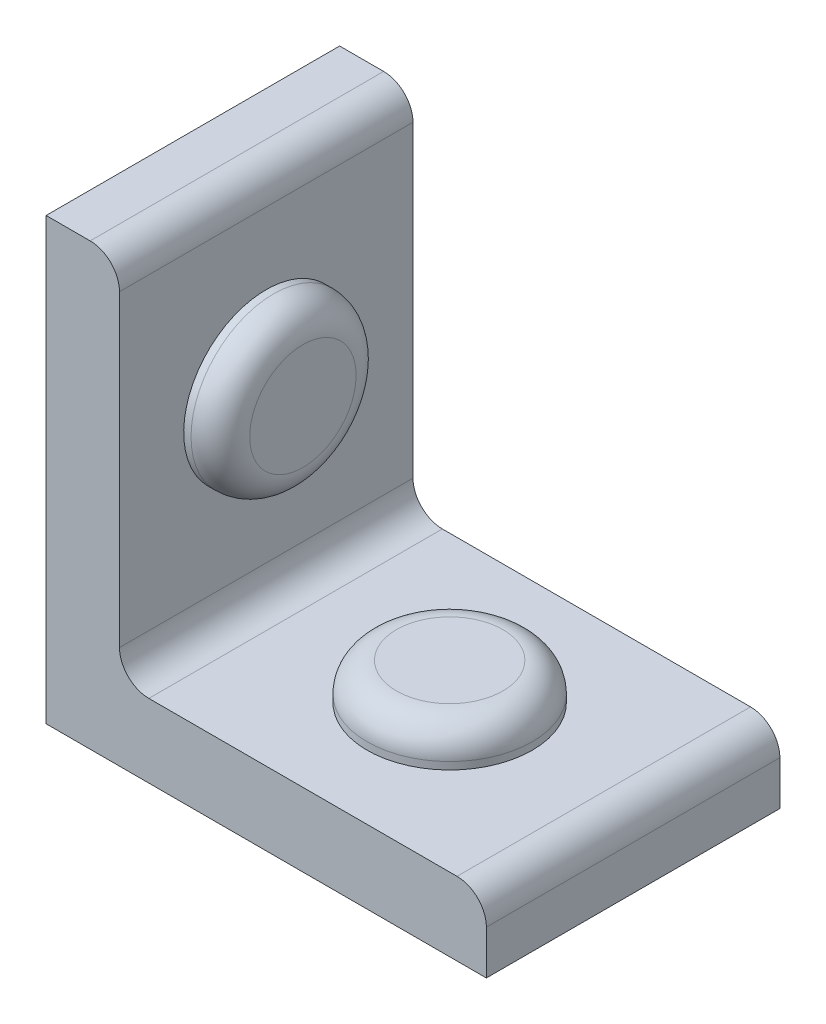
SolidWorks part; units mm, degrees
ref_plane "Front Plane" through (0, 0, 0) normal (0, 0, 1) x (1, 0, 0)
ref_plane "Top Plane" through (0, 0, 0) normal (0, 1, 0) x (1, 0, 0)
ref_plane "Right Plane" through (0, 0, 0) normal (1, 0, 0) x (0, 0, -1)
sketch "Sketch1" plane through (0, 0, 0) normal (0, 0, 1) x (1, 0, 0)
  line L0 (0, 0) -> (38.1, 0)
  line L1 (38.1, 0) -> (38.1, 3.81)
  line L2 (35.56, 6.35) -> (8.89, 6.35)
  line L3 (6.35, 8.89) -> (6.35, 35.56)
  line L4 (3.81, 38.1) -> (0, 38.1)
  line L5 (0, 38.1) -> (0, 0)
  arc A0 (8.89, 6.35) -> (6.35, 8.89) centre (8.89, 8.89) cw
  arc A1 (6.35, 35.56) -> (3.81, 38.1) centre (3.81, 35.56) ccw
  arc A2 (38.1, 3.81) -> (35.56, 6.35) centre (35.56, 3.81) ccw
  point P11 (6.35, 38.1)
  point P14 (38.1, 6.35)
  dimension "D5" = 2.54
  dimension "D1" = 6.35
  dimension "D2" = 6.35
  dimension "D3" = 38.1
  dimension "D4" = 38.1
extrude "Boss-Extrude1" add sketch "Sketch1" along normal blind 25.4
sketch "Sketch2" plane through (0, 6.35, 0) normal (0, 1, 0) x (1, 0, 0)
  line L0 (35.56, 0) -> (8.89, -25.4)
  line L1 (8.89, 0) -> (35.56, -25.4)
  circle A0 centre (22.225, -12.7) radius 7.1438
  point P10 (22.225, -12.7)
  dimension "D1" = 14.2875
extrude "Boss-Extrude2" add sketch "Sketch2" along normal blind 3.175 contours A0
fillet "Fillet1" radius 2.54 1 edges at (15.0813, 9.525, 12.7)
sketch "Sketch3" plane through (6.35, 0, 0) normal (1, 0, 0) x (0, 0, -1)
  line L0 (0, 35.56) -> (-25.4, 8.89) construction
  line L1 (-25.4, 8.89) -> (-25.4, 35.56) construction
  line L2 (-25.4, 35.56) -> (0, 8.89) construction
  circle A0 centre (-12.7, 22.225) radius 7.1438
  dimension "D1" = 14.2875
extrude "Boss-Extrude3" add sketch "Sketch3" along normal blind 3.175
fillet "Fillet2" radius 2.54 1 edges at (9.525, 29.3687, 12.7)
